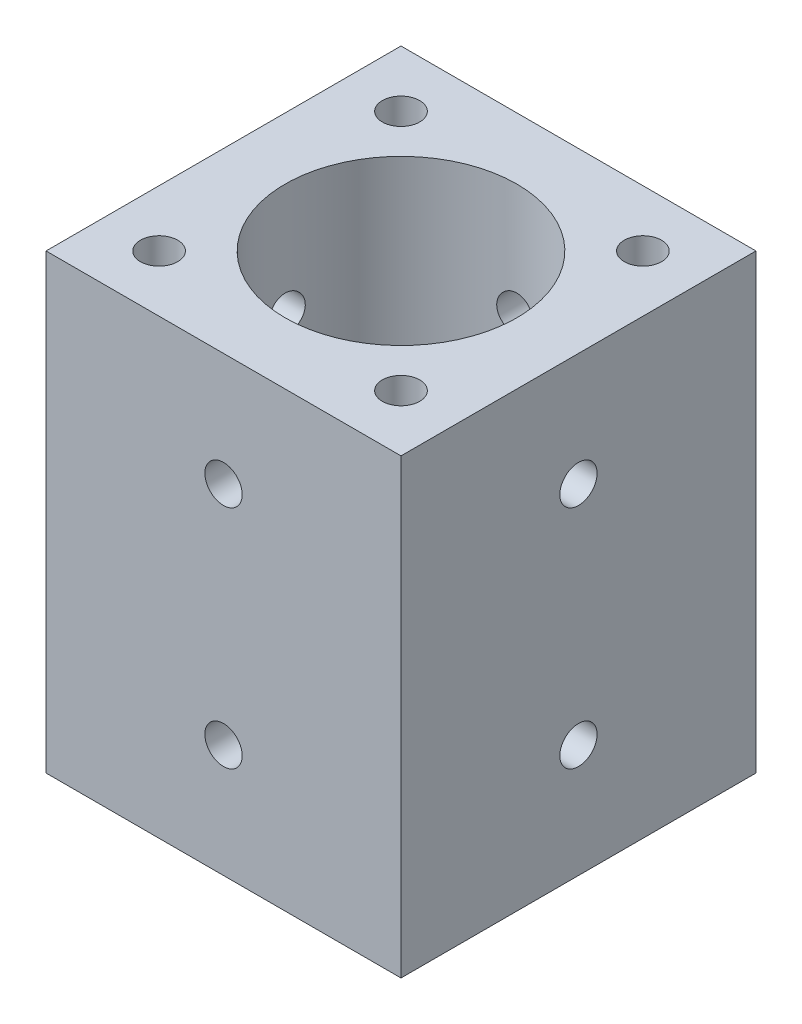
SolidWorks part; units mm, degrees
material "3003 Alloy"
ref_plane "Front Plane" through (0, 0, 0) normal (0, 0, 1) x (1, 0, 0)
ref_plane "Top Plane" through (0, 0, 0) normal (0, 1, 0) x (1, 0, 0)
ref_plane "Right Plane" through (0, 0, 0) normal (1, 0, 0) x (0, 0, -1)
sketch "Sketch1" plane through (0, 0, 0) normal (0, 1, 0) x (1, 0, 0)
  line L0 (-15.7, 0) -> (0, 0) construction
  line L1 (-15.7, 15.7) -> (15.7, 15.7)
  line L2 (-15.7, 15.7) -> (-15.7, -15.7)
  line L3 (-15.7, -15.7) -> (15.7, -15.7)
  line L4 (15.7, 15.7) -> (15.7, -15.7)
  line L5 (0, 0) -> (0, 15.7) construction
  circle A0 centre (0, 0) radius 10.25
  dimension "D3" = 20.5
  dimension "D1" = 31.4
  dimension "D2" = 31.4
extrude "Boss-Extrude1" add sketch "Sketch1" along normal blind 40
sketch "Sketch2" plane through (15.7, 0, 0) normal (1, 0, 0) x (0, 0, -1)
  line L0 (0, 40) -> (0, 0) construction
  line L1 (-15.7, 40) -> (15.7, 40) construction
  line L2 (-15.7, 0) -> (15.7, 0) construction
  line L3 (-15.7, 20) -> (15.7, 20) construction
  line L4 (-15.7, 40) -> (-15.7, 0) construction
  line L5 (15.7, 40) -> (15.7, 0) construction
  circle A0 centre (0, 30) radius 1.5
  circle A1 centre (0, 10) radius 1.5
  dimension "D1" = 3
  dimension "D2" = 20
extrude "Cut-Extrude1" cut sketch "Sketch2" against normal blind 40
hole_wizard "M4 Tapped Hole1" positions "3DSketch1" profile "Sketch3" tap size "M4" standard "DIN"
sketch3d "3DSketch1"
  line L0 (-15.7, 10, 0) -> (-10.1396, 10, 0) construction
  line L1 (-15.7, 30, 0) -> (-10.1396, 30, 0) construction
  line L2 (10.1396, 30, 0) -> (15.7, 30, 0) construction
  line L3 (10.1396, 10, 0) -> (15.7, 10, 0) construction
  point P0 (-15.7, 10, 0)
  point P4 (-15.7, 30, 0)
  point P8 (15.7, 30, 0)
  point P12 (15.7, 10, 0)
sketch "Sketch3" plane through (-15.7, 10, 0) normal (0, 1, 0) x (0, 0, 1)
  line L0 (0, 0) -> (0, 11.0914)
  line L1 (0, 11.0914) -> (1.65, 10.1)
  line L2 (1.65, 10.1) -> (1.65, 0)
  line L5 (1.65, 0) -> (0, 0)
  line L10 (0, 11.0914) -> (-1.65, 10.1) construction
  line L11 (0, -6.35) -> (0, 107.95) construction
  dimension "Tap Drill Dia." = 3.3
  dimension "Tap Drill Depth" = 10.1
  dimension "Drill Angle" = 118
cosmetic thread "Hole Thread1" parameters "D1"=8, "D2"=4
cosmetic thread "Hole Thread2" parameters "D1"=8, "D2"=4
cosmetic thread "Hole Thread3" parameters "D1"=8, "D2"=4
cosmetic thread "Hole Thread4" parameters "D1"=8, "D2"=4
sketch "Sketch5" plane through (0, 0, 15.7) normal (0, 0, 1) x (1, 0, 0)
  line L0 (0, 40) -> (0, 0) construction
  line L1 (-15.7, 40) -> (15.7, 40) construction
  line L2 (0, 20) -> (15.7, 20) construction
  line L3 (15.7, 40) -> (15.7, 0) construction
  circle A0 centre (0, 30) radius 1.5
  circle A1 centre (0, 10) radius 1.5
  dimension "D1" = 3
  dimension "D2" = 20
extrude "Cut-Extrude2" cut sketch "Sketch5" against normal blind 40
hole_wizard "M4 Tapped Hole2" positions "3DSketch2" profile "Sketch6" tap size "M4" standard "DIN"
sketch3d "3DSketch2"
  line L0 (0, 30, 10.1396) -> (0, 30, 15.7) construction
  line L1 (0, 30, -15.7) -> (0, 30, -10.25) construction
  line L2 (0, 10, 10.1396) -> (0, 10, 15.7) construction
  line L3 (0, 10, -15.7) -> (0, 10, -10.25) construction
  point P0 (0, 30, 15.7)
  point P4 (0, 30, -15.7)
  point P9 (0, 10, 15.7)
  point P13 (0, 10, -15.7)
sketch "Sketch6" plane through (0, 30, 15.7) normal (1, 0, 0) x (0, -1, 0)
  line L0 (0, 0) -> (0, 11.0914)
  line L1 (0, 11.0914) -> (1.65, 10.1)
  line L2 (1.65, 10.1) -> (1.65, 0)
  line L5 (1.65, 0) -> (0, 0)
  line L10 (0, 11.0914) -> (-1.65, 10.1) construction
  line L11 (0, -6.35) -> (0, 107.95) construction
  dimension "Tap Drill Dia." = 3.3
  dimension "Tap Drill Depth" = 10.1
  dimension "Drill Angle" = 118
cosmetic thread "Hole Thread5" parameters "D1"=8, "D2"=4
cosmetic thread "Hole Thread6" parameters "D1"=8, "D2"=4
cosmetic thread "Hole Thread11" parameters "D1"=8, "D2"=4
cosmetic thread "Hole Thread12" parameters "D1"=8, "D2"=4
sketch "Sketch8" plane through (0, 0, 0) normal (0, -1, 0) x (1, 0, 0)
  line L0 (0, -10.7) -> (0, 0) construction
  line L1 (10.7, -10.7) -> (-10.7, -10.7) construction
  line L2 (10.7, -10.7) -> (10.7, 10.7) construction
  line L3 (10.7, 10.7) -> (-10.7, 10.7) construction
  line L4 (-10.7, -10.7) -> (-10.7, 10.7) construction
  line L5 (0, 0) -> (-10.7, 0) construction
  line L6 (-15.7, 15.7) -> (15.7, 15.7) construction
  line L7 (-15.7, -15.7) -> (-15.7, 15.7) construction
  circle A0 centre (-10.7, 10.7) radius 1.5
  circle A1 centre (10.7, 10.7) radius 1.5
  circle A2 centre (10.7, -10.7) radius 1.5
  circle A3 centre (-10.7, -10.7) radius 1.5
  dimension "D1" = 3
  dimension "D2" = 5
  dimension "D3" = 5
extrude "Cut-Extrude3" cut sketch "Sketch8" against normal blind 30
hole_wizard "M4 Tapped Hole3" positions "3DSketch3" profile "Sketch9" tap size "M4" standard "DIN"
sketch3d "3DSketch3"
  line L0 (-10.7, 30, 10.7) -> (-10.7, 0, 10.7) construction
  line L1 (10.7, 30, 10.7) -> (10.7, 0, 10.7) construction
  line L2 (10.7, 30, -10.7) -> (10.7, 0, -10.7) construction
  line L3 (-10.7, 30, -10.7) -> (-10.7, 0, -10.7) construction
  point P0 (-10.7, 0, 10.7)
  point P4 (10.7, 0, 10.7)
  point P8 (10.7, 0, -10.7)
  point P12 (-10.7, 0, -10.7)
sketch "Sketch9" plane through (-10.7, 0, 10.7) normal (1, 0, 0) x (0, 0, -1)
  line L0 (0, 0) -> (0, 53.0914)
  line L1 (0, 53.0914) -> (1.65, 52.1)
  line L2 (1.65, 52.1) -> (1.65, 0)
  line L5 (1.65, 0) -> (0, 0)
  line L10 (0, 53.0914) -> (-1.65, 52.1) construction
  line L11 (0, -6.35) -> (0, 107.95) construction
  dimension "Tap Drill Dia." = 3.3
  dimension "Tap Drill Depth" = 52.1
  dimension "Drill Angle" = 118
cosmetic thread "Hole Thread7" parameters "D1"=40, "D2"=4
cosmetic thread "Hole Thread8" parameters "D1"=40, "D2"=4
cosmetic thread "Hole Thread9" parameters "D1"=40, "D2"=4
cosmetic thread "Hole Thread10" parameters "D1"=40, "D2"=4
